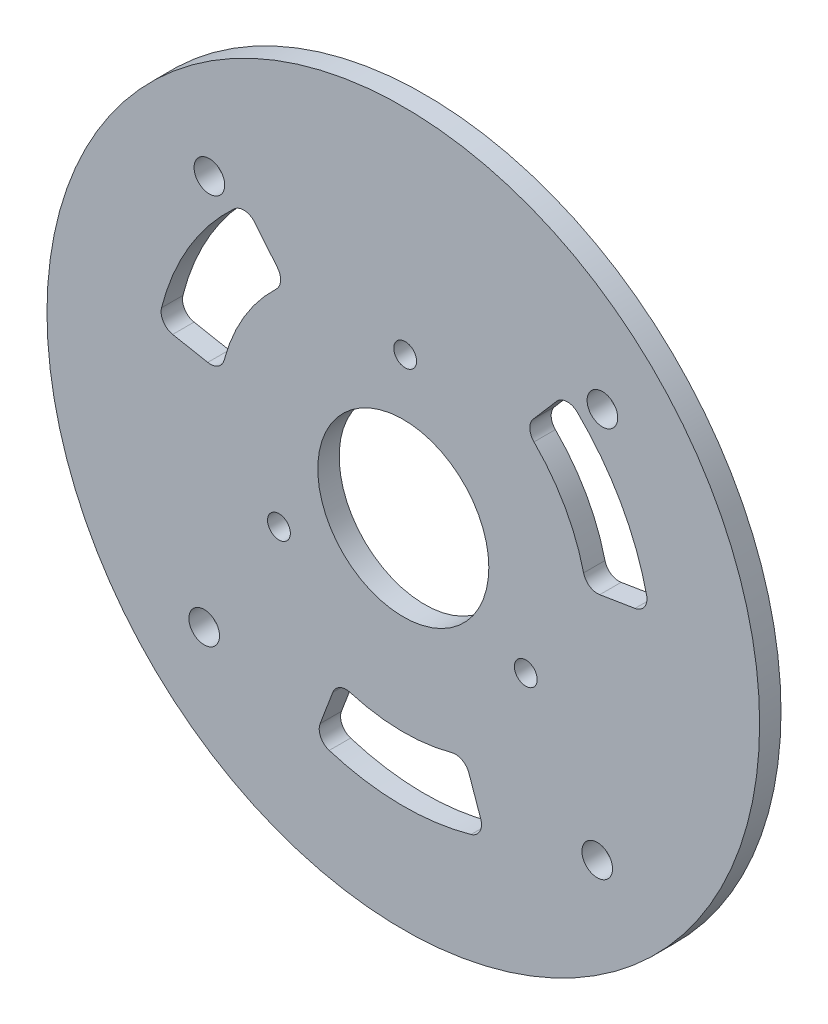
SolidWorks part; units mm, degrees
ref_plane "前视基准面" through (0, 0, 0) normal (0, 0, 1) x (1, 0, 0)
ref_plane "上视基准面" through (0, 0, 0) normal (0, 1, 0) x (1, 0, 0)
ref_plane "右视基准面" through (0, 0, 0) normal (1, 0, 0) x (0, 0, -1)
sketch "草图1" plane through (0, 0, 0) normal (0, 0, 1) x (1, 0, 0)
  circle A0 centre (0, 0) radius 50
  circle A1 centre (0, 0) radius 12
  dimension "D1" = 100
  dimension "D2" = 24
extrude "凸台-拉伸1" add sketch "草图1" along normal blind 3
sketch "草图2" plane through (0, 0, 3) normal (0, 0, 1) x (1, 0, 0)
  line L1 (-17.4508, -9.7708) -> (17.1872, -10.2275)
  line L2 (17.1872, -10.2275) -> (0.2637, 19.9983)
  line L3 (0.2637, 19.9983) -> (-17.4508, -9.7708)
  circle A0 centre (0, 0) radius 10 construction
  circle A1 centre (0.2637, 19.9983) radius 1.6
  circle A2 centre (17.1872, -10.2275) radius 1.6
  circle A3 centre (-17.4508, -9.7708) radius 1.6
  dimension "D1" = 20
  dimension "D2" = 3.2
  dimension "D3" = 19.9983
extrude "切除-拉伸1" cut sketch "草图2" against normal through all contours A1 | A2 | A3
sketch "草图4" plane through (0, 0, 0) normal (0, 0, -1) x (-1, 0, 0)
  line L0 (16.4484, 20.1358) -> (22.1421, 27.1058)
  line L1 (25.5433, 4.852) -> (34.3851, 6.5316)
  arc A0 (25.5433, 4.852) -> (16.4484, 20.1358) centre (0, 0) ccw
  arc A1 (34.3851, 6.5316) -> (22.1421, 27.1058) centre (0, 0) ccw
  dimension "D1" = 52
  dimension "D2" = 70
  dimension "D4" = 40
  dimension "D5" = 9
extrude "切除-拉伸3" cut sketch "草图4" against normal through all
fillet "圆角1" radius 2 4 edges at (-25.5433, 4.852, 1.5) (-16.4484, 20.1358, 1.5) (-34.3851, 6.5316, 1.5) (-22.1421, 27.1058, 1.5)
pattern_circular "阵列(圆周)2" count 3 every 120 about axis through (0, 0, 0) along (0, 0, 1) of "圆角1", "切除-拉伸3"
sketch "草图5" plane through (0, 0, 0) normal (0, 0, 1) x (1, 0, 0)
  circle A1 centre (27.9383, 27.2112) radius 2.15
  circle A2 centre (27.2112, -27.9383) radius 2.15
  circle A3 centre (-27.9383, -27.2112) radius 2.15
  circle A4 centre (-27.2112, 27.9383) radius 2.15
  point P16 (0, 0)
  dimension "D2" = 4
extrude "切除-拉伸4" cut sketch "草图5" along normal blind 10
